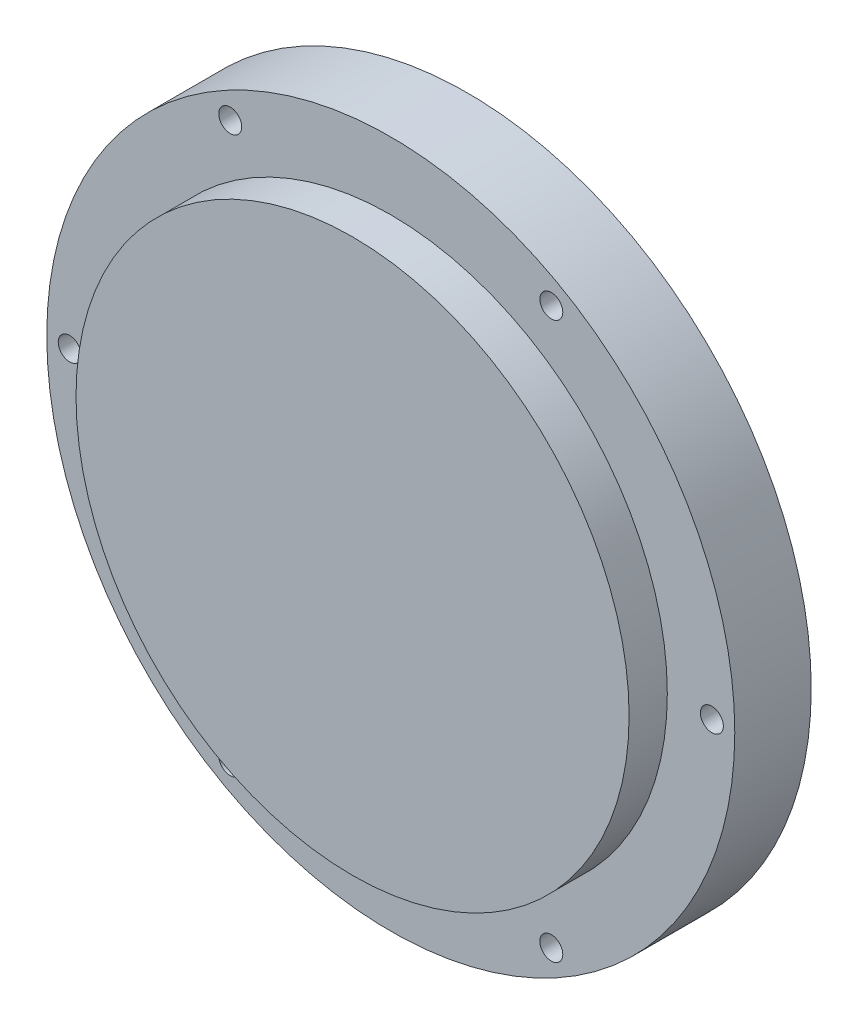
SolidWorks part; units mm, degrees
ref_plane "Front Plane" through (0, 0, 0) normal (0, 0, 1) x (1, 0, 0)
ref_plane "Top Plane" through (0, 0, 0) normal (0, 1, 0) x (1, 0, 0)
ref_plane "Right Plane" through (0, 0, 0) normal (1, 0, 0) x (0, 0, -1)
sketch "Sketch1" plane through (0, 0, 0) normal (0, 0, 1) x (1, 0, 0)
  circle A0 centre (0, 0) radius 45
  dimension "D1" = 90
extrude "Boss-Extrude1" add sketch "Sketch1" along normal mid plane 10
sketch "Sketch2" plane through (0, 0, 5) normal (0, 0, 1) x (1, 0, 0)
  circle A0 centre (0, 0) radius 36.175
  dimension "D1" = 72.35
extrude "Boss-Extrude2" add sketch "Sketch2" along normal mid plane 10
sketch "Sketch4" plane through (0, 0, -5) normal (0, 0, -1) x (-1, 0, 0)
  circle A0 centre (-42, 0) radius 1.5
  circle A1 centre (-21, 36.3731) radius 1.5
  circle A2 centre (21, 36.3731) radius 1.5
  circle A3 centre (42, 0) radius 1.5
  circle A4 centre (21, -36.3731) radius 1.5
  circle A5 centre (-21, -36.3731) radius 1.5
  point P16 (0, 0)
  dimension "D1" = 3
  dimension "D2" = 42
  dimension "D3" = 6
extrude "Cut-Extrude2" cut sketch "Sketch4" against normal through all
